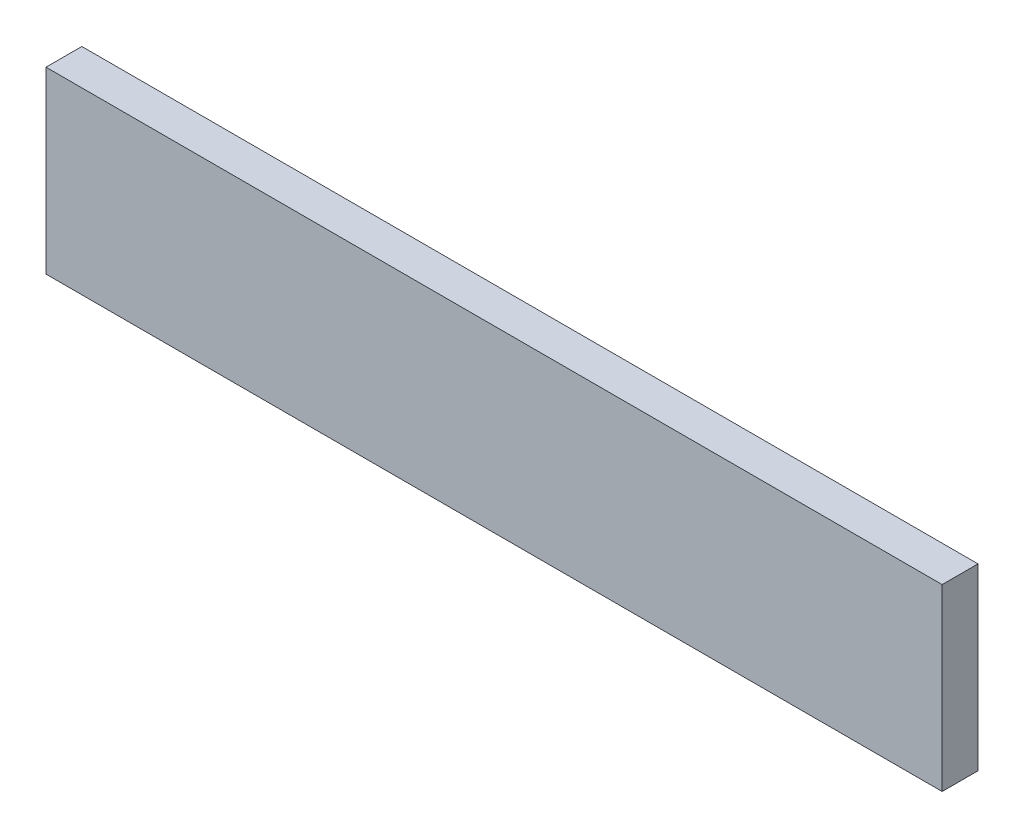
SolidWorks part; units mm, degrees
ref_plane "Front Plane" through (0, 0, 0) normal (0, 0, 1) x (1, 0, 0)
ref_plane "Top Plane" through (0, 0, 0) normal (0, 1, 0) x (1, 0, 0)
ref_plane "Right Plane" through (0, 0, 0) normal (1, 0, 0) x (0, 0, -1)
sketch "Sketch1" plane through (0, 0, 0) normal (0, 0, 1) x (1, 0, 0)
  line L1 (-74.5636, 61.2942) -> (425.4364, 61.2942)
  line L2 (-74.5636, 61.2942) -> (-74.5636, -38.7058)
  line L3 (-74.5636, -38.7058) -> (425.4364, -38.7058)
  line L4 (425.4364, 61.2942) -> (425.4364, -38.7058)
extrude "Boss-Extrude1" add sketch "Sketch1" along normal blind 20
